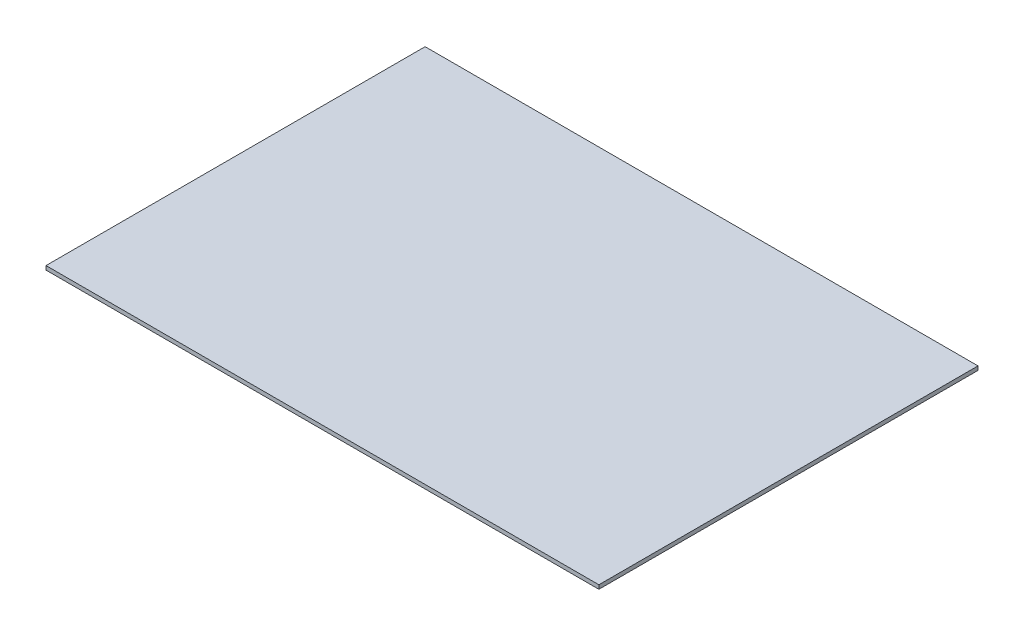
SolidWorks part; units mm, degrees
ref_plane "Front Plane" through (0, 0, 0) normal (0, 0, 1) x (1, 0, 0)
ref_plane "Top Plane" through (0, 0, 0) normal (0, 1, 0) x (1, 0, 0)
ref_plane "Right Plane" through (0, 0, 0) normal (1, 0, 0) x (0, 0, -1)
sketch "Sketch1" plane through (0, 0, 0) normal (0, 1, 0) x (1, 0, 0)
  line L1 (-444.5, -304.8) -> (444.5, -304.8)
  line L2 (-444.5, -304.8) -> (-444.5, 304.8)
  line L3 (-444.5, 304.8) -> (444.5, 304.8)
  line L4 (444.5, -304.8) -> (444.5, 304.8)
  line L5 (-444.5, -304.8) -> (444.5, 304.8) construction
  line L6 (-444.5, 304.8) -> (444.5, -304.8) construction
  point P0 (0, 0)
  dimension "D1" = 889
  dimension "D2" = 609.6
extrude "Boss-Extrude1" add sketch "Sketch1" along normal blind 6.35
